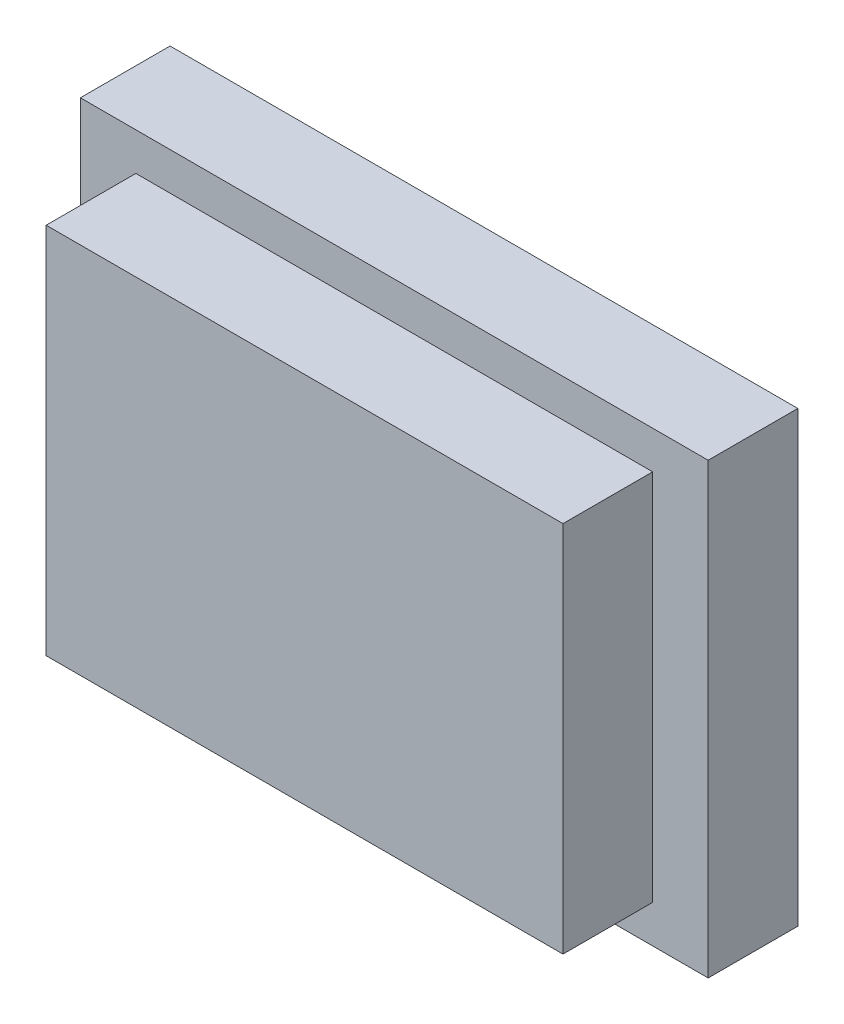
SolidWorks part; units mm, degrees
ref_plane "Front Plane" through (0, 0, 0) normal (0, 0, 1) x (1, 0, 0)
ref_plane "Top Plane" through (0, 0, 0) normal (0, 1, 0) x (1, 0, 0)
ref_plane "Right Plane" through (0, 0, 0) normal (1, 0, 0) x (0, 0, -1)
sketch "Sketch1" plane through (0, 0, 0) normal (0, 0, 1) x (1, 0, 0)
  line L1 (-10.5, -7.5) -> (10.5, -7.5)
  line L2 (-10.5, -7.5) -> (-10.5, 7.5)
  line L3 (-10.5, 7.5) -> (10.5, 7.5)
  line L4 (10.5, -7.5) -> (10.5, 7.5)
  line L5 (-10.5, -7.5) -> (10.5, 7.5) construction
  line L6 (-10.5, 7.5) -> (10.5, -7.5) construction
  point P0 (0, 0)
  dimension "D1" = 21
  dimension "D2" = 15
extrude "Boss-Extrude1" add sketch "Sketch1" along normal blind 3
sketch "Sketch2" plane through (0, 0, 3) normal (0, 0, 1) x (1, 0, 0)
  line L1 (-8.6442, -6.2363) -> (8.6442, -6.2363)
  line L2 (-8.6442, -6.2363) -> (-8.6442, 6.2363)
  line L3 (-8.6442, 6.2363) -> (8.6442, 6.2363)
  line L4 (8.6442, -6.2363) -> (8.6442, 6.2363)
  line L5 (-8.6442, -6.2363) -> (8.6442, 6.2363) construction
  line L6 (-8.6442, 6.2363) -> (8.6442, -6.2363) construction
  point P0 (0, 0)
extrude "Boss-Extrude2" add sketch "Sketch2" along normal blind 3
